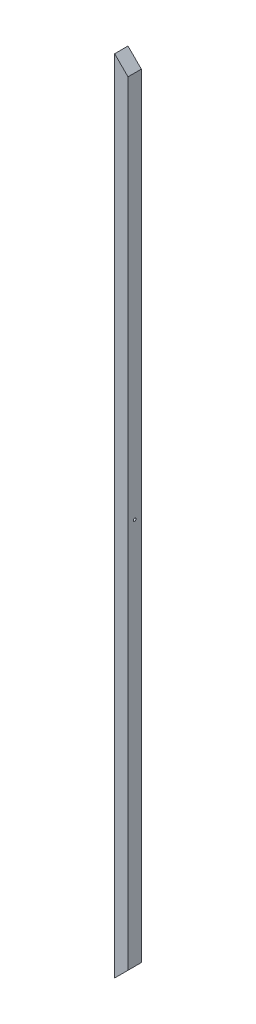
SolidWorks part; units mm, degrees
ref_plane "Спереди" through (0, 0, 0) normal (0, 0, 1) x (1, 0, 0)
ref_plane "Сверху" through (0, 0, 0) normal (0, 1, 0) x (1, 0, 0)
ref_plane "Справа" through (0, 0, 0) normal (1, 0, 0) x (0, 0, -1)
other "Configuration Table"
sketch "Эскиз1" plane through (0, 0, 0) normal (0, 1, 0) x (1, 0, 0)
  line L1 (25, 25) -> (-25, 25)
  line L2 (25, 25) -> (25, -25)
  line L3 (25, -25) -> (-25, -25)
  line L4 (-25, 25) -> (-25, -25)
  line L5 (25, 25) -> (-25, -25) construction
  line L6 (25, -25) -> (-25, 25) construction
  point P0 (0, 0)
extrude "Бобышка-Вытянуть1" add sketch "Эскиз1" along normal blind 3000
sketch "Эскиз2" plane through (0, 0, 25) normal (0, 0, 1) x (1, 0, 0)
  line L0 (25, 3000) -> (-25, 3000)
  line L1 (-25, 3000) -> (25, 2950)
  line L2 (25, 3000) -> (25, 0) construction
  line L3 (25, 2950) -> (25, 3000)
  line L4 (25, 0) -> (-25, 0)
  line L5 (-25, 0) -> (25, 50)
  line L6 (25, 50) -> (25, 0)
extrude "Вырез-Вытянуть1" cut sketch "Эскиз2" against normal blind 3000
sketch "Эскиз4" plane through (-25, 0, 0) normal (-1, 0, 0) x (0, 0, 1)
  line L0 (0, 3000) -> (0, 0) construction
  line L1 (-25, 3000) -> (25, 3000) construction
  circle A0 centre (0, 1500) radius 5
extrude "Вырез-Вытянуть2" cut sketch "Эскиз4" against normal blind 50
